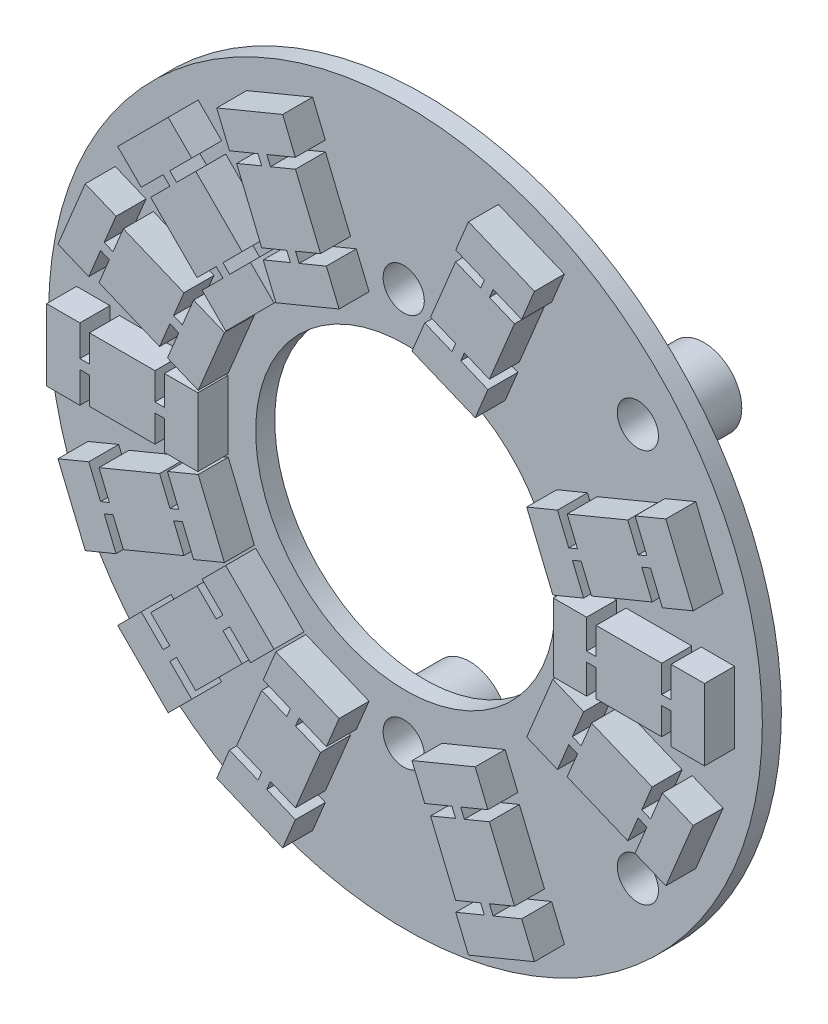
SolidWorks part; units mm, degrees
ref_plane "Front Plane" through (0, 0, 0) normal (0, 0, 1) x (1, 0, 0)
ref_plane "Top Plane" through (0, 0, 0) normal (0, 1, 0) x (1, 0, 0)
ref_plane "Right Plane" through (0, 0, 0) normal (1, 0, 0) x (0, 0, -1)
sketch "Sketch3" plane through (0, 0, 0) normal (0, 0, 1) x (1, 0, 0)
  line L12 (-1.6171, 12.9824) -> (-3.5525, 12.9824)
  line L13 (9.3448, 12.9824) -> (-1.6171, 12.9824)
  line L14 (10.3034, 12.9824) -> (9.3448, 12.9824)
  line L15 (12.3651, 9.967) -> (12.3651, 10.9208)
  line L16 (12.3651, -9.7668) -> (12.3651, 9.967)
  line L17 (12.3651, -10.7265) -> (12.3651, -9.7668)
  line L18 (9.3576, -12.7882) -> (10.3034, -12.7882)
  line L19 (-3.5398, -12.7882) -> (-1.6299, -12.7882)
  line L20 (-1.6299, -12.7882) -> (9.3576, -12.7882)
  line L21 (-10.1708, -12.7882) -> (-3.5398, -12.7882)
  line L22 (-12.2325, 10.9208) -> (-12.2325, -10.7265)
  line L23 (-3.5525, 12.9824) -> (-10.1708, 12.9824)
  line L34 (9.5245, 6.1678) -> (5.7246, 6.1678)
  line L35 (9.7306, -3.0873) -> (9.7306, 5.9617)
  line L36 (5.7246, -3.2934) -> (9.5245, -3.2934)
  line L37 (5.5184, 5.9617) -> (5.5184, -3.0873)
  line L38 (1.5664, -2.5118) -> (5.5184, -2.5118)
  line L39 (5.5184, 3.2608) -> (1.5664, 3.2608)
  line L40 (1.6413, -4.0348) -> (1.6413, 4.2118)
  line L41 (-6.6053, -4.0348) -> (1.6413, -4.0348)
  line L42 (-6.6053, 4.2118) -> (-6.6053, -4.0348)
  line L43 (1.6413, 4.2118) -> (-6.6053, 4.2118)
  circle A0 centre (-2.482, 0.0885) radius 19.05
  circle A1 centre (-2.5789, -10.4031) radius 1.1 construction
  circle A2 centre (9.9211, -10.4031) radius 1.1 construction
  circle A3 centre (-2.5789, 10.5969) radius 1.1 construction
  circle A4 centre (9.9211, 10.5969) radius 1.1 construction
  circle A5 centre (-2.5789, -10.4031) radius 1.1
  circle A6 centre (9.9211, -10.4031) radius 1.1
  circle A7 centre (-2.5789, 10.5969) radius 1.1
  arc A12 (12.3651, 10.9208) -> (10.3034, 12.9824) centre (10.3034, 10.9208) ccw
  arc A13 (10.3034, -12.7882) -> (12.3651, -10.7265) centre (10.3034, -10.7265) ccw
  arc A14 (-12.2325, -10.7265) -> (-10.1708, -12.7882) centre (-10.1708, -10.7265) ccw
  arc A15 (-10.1708, 12.9824) -> (-12.2325, 10.9208) centre (-10.1708, 10.9208) ccw
  circle A16 centre (9.9211, 10.5969) radius 1.1
  circle A21 centre (-2.482, 0.0885) radius 3.2986
  arc A22 (5.7246, 6.1678) -> (5.5184, 5.9617) centre (5.7246, 5.9617) ccw
  arc A23 (9.7306, 5.9617) -> (9.5245, 6.1678) centre (9.5245, 5.9617) ccw
  arc A24 (9.5245, -3.2934) -> (9.7306, -3.0873) centre (9.5245, -3.0873) ccw
  arc A25 (5.5184, -3.0873) -> (5.7246, -3.2934) centre (5.7246, -3.0873) ccw
  circle A26 centre (-2.482, 0.0885) radius 8.0005
  dimension "D1" = 38.1
extrude "Boss-Extrude1" add sketch "Sketch3" along normal blind 1.016
sketch "Sketch4" plane through (0, 0, 0) normal (0, 0, 1) x (1, 0, 0)
  line L0 (-21.532, 0.0885) -> (-10.4825, 0.0885) construction
  line L1 (-15.8231, 8.1122) -> (-12.5895, 6.7728)
  line L2 (-17.7572, -1.6115) -> (-14.2572, -1.6115)
  line L3 (-17.7572, -1.6115) -> (-17.7572, 1.7885)
  line L4 (-17.7572, 1.7885) -> (-14.2572, 1.7885)
  line L5 (-14.2572, -1.6115) -> (-14.2572, 1.7885)
  line L6 (-17.7572, -1.6115) -> (-14.2572, 1.7885) construction
  line L7 (-17.7572, 1.7885) -> (-14.2572, -1.6115) construction
  line L8 (-17.1242, 4.971) -> (-15.8231, 8.1122)
  line L9 (-17.1242, 4.971) -> (-13.8906, 3.6316)
  line L10 (-13.8906, 3.6316) -> (-12.5895, 6.7728)
  line L11 (-11.6162, 13.2144) -> (-9.1413, 10.7395)
  line L12 (-14.0203, 10.8102) -> (-11.6162, 13.2144)
  line L13 (-14.0203, 10.8102) -> (-11.5455, 8.3353)
  line L14 (-11.5455, 8.3353) -> (-9.1413, 10.7395)
  line L15 (-5.777, 16.3182) -> (-4.4376, 13.0847)
  line L16 (-8.9182, 15.0171) -> (-5.777, 16.3182)
  line L17 (-8.9182, 15.0171) -> (-7.5788, 11.7835)
  line L18 (-7.5788, 11.7835) -> (-4.4376, 13.0847)
  line L19 (0.8055, 16.9513) -> (0.8055, 13.4513) [skipped]
  line L20 (-2.5945, 16.9513) -> (0.8055, 16.9513) [skipped]
  line L21 (-2.5945, 16.9513) -> (-2.5945, 13.4513) [skipped]
  line L22 (-2.5945, 13.4513) -> (0.8055, 13.4513) [skipped]
  line L23 (7.1292, 15.0171) -> (5.7898, 11.7835)
  line L24 (3.988, 16.3182) -> (7.1292, 15.0171)
  line L25 (3.988, 16.3182) -> (2.6486, 13.0847)
  line L26 (2.6486, 13.0847) -> (5.7898, 11.7835)
  line L27 (12.2313, 10.8102) -> (9.7565, 8.3353) [skipped]
  line L28 (9.8272, 13.2144) -> (12.2313, 10.8102) [skipped]
  line L29 (9.8272, 13.2144) -> (7.3523, 10.7395) [skipped]
  line L30 (7.3523, 10.7395) -> (9.7565, 8.3353) [skipped]
  line L31 (15.3352, 4.971) -> (12.1016, 3.6316)
  line L32 (14.0341, 8.1122) -> (15.3352, 4.971)
  line L33 (14.0341, 8.1122) -> (10.8005, 6.7728)
  line L34 (10.8005, 6.7728) -> (12.1016, 3.6316)
  line L35 (15.9682, -1.6115) -> (12.4682, -1.6115)
  line L36 (15.9682, 1.7885) -> (15.9682, -1.6115)
  line L37 (15.9682, 1.7885) -> (12.4682, 1.7885)
  line L38 (12.4682, 1.7885) -> (12.4682, -1.6115)
  line L39 (14.0341, -7.9351) -> (10.8005, -6.5957)
  line L40 (15.3352, -4.7939) -> (14.0341, -7.9351)
  line L41 (15.3352, -4.7939) -> (12.1016, -3.4546)
  line L42 (12.1016, -3.4546) -> (10.8005, -6.5957)
  line L43 (9.8272, -13.0373) -> (7.3523, -10.5624) [skipped]
  line L44 (12.2313, -10.6331) -> (9.8272, -13.0373) [skipped]
  line L45 (12.2313, -10.6331) -> (9.7565, -8.1583) [skipped]
  line L46 (9.7565, -8.1583) -> (7.3523, -10.5624) [skipped]
  line L47 (3.988, -16.1411) -> (2.6486, -12.9076)
  line L48 (7.1292, -14.84) -> (3.988, -16.1411)
  line L49 (7.1292, -14.84) -> (5.7898, -11.6064)
  line L50 (5.7898, -11.6064) -> (2.6486, -12.9076)
  line L51 (-2.5945, -16.7742) -> (-2.5945, -13.2742) [skipped]
  line L52 (0.8055, -16.7742) -> (-2.5945, -16.7742) [skipped]
  line L53 (0.8055, -16.7742) -> (0.8055, -13.2742) [skipped]
  line L54 (0.8055, -13.2742) -> (-2.5945, -13.2742) [skipped]
  line L55 (-8.9182, -14.84) -> (-7.5788, -11.6064)
  line L56 (-5.777, -16.1411) -> (-8.9182, -14.84)
  line L57 (-5.777, -16.1411) -> (-4.4376, -12.9076)
  line L58 (-4.4376, -12.9076) -> (-7.5788, -11.6064)
  line L59 (-14.0203, -10.6331) -> (-11.5455, -8.1583)
  line L60 (-11.6162, -13.0373) -> (-14.0203, -10.6331)
  line L61 (-11.6162, -13.0373) -> (-9.1413, -10.5624)
  line L62 (-9.1413, -10.5624) -> (-11.5455, -8.1583)
  line L63 (-17.1242, -4.7939) -> (-13.8906, -3.4546)
  line L64 (-15.8231, -7.9351) -> (-17.1242, -4.7939)
  line L65 (-15.8231, -7.9351) -> (-12.5895, -6.5957)
  line L66 (-12.5895, -6.5957) -> (-13.8906, -3.4546)
  line L67 (-0.8945, 0.0885) -> (-14.2572, 1.7885) construction
  line L68 (-0.8945, 0.0885) -> (-12.5895, 6.7728) construction
  circle A0 centre (-2.482, 0.0885) radius 19.05 construction
  circle A1 centre (-2.482, 0.0885) radius 8.0005 construction
  point P7 (-16.0072, 0.0885)
  dimension "D1" = 3.5
  dimension "D2" = 3.4
  dimension "D4" = 22.5
  dimension "D3" = 16
sketch "Sketch5" plane through (-0.0742, 0.0026, -3.44) normal (0, 0, 1) x (1, 0, 0)
  circle A0 centre (-2.5047, 10.5942) radius 1.1
  circle A1 centre (9.9953, 10.5942) radius 1.1
  circle A2 centre (9.9953, -10.4058) radius 1.1
  circle A3 centre (-2.5047, -10.4058) radius 1.1
  circle A4 centre (-2.5047, -10.4058) radius 2.032
  circle A5 centre (9.9953, -10.4058) radius 2.032
  circle A6 centre (-2.5047, 10.5942) radius 2.032
  circle A7 centre (9.9953, 10.5942) radius 2.032
  dimension "D1" = 4.064
  dimension "D2" = 4.064
  dimension "D3" = 4.064
  dimension "D4" = 4.064
extrude "Boss-Extrude3" add sketch "Sketch5" against normal blind 2.5 from surface at 3.44 contours A6 | A7 | A5 | A4 | A1 | A0 | A3 | A2 starting at face at (5.5184, 0.0885, 0)
sketch "Sketch9" plane through (0, 0, 0) normal (0, 0, 1) x (1, 0, 0)
  line L0 (-10.4825, 0.0885) -> (-21.532, 0.0885) construction
  line L1 (-21.4402, 0.0885) -> (-20.9322, 0.0885) construction
  line L2 (-17.7572, -1.6115) -> (-14.2572, -1.6115)
  line L3 (-17.7572, -1.6115) -> (-17.7572, -0.1655)
  line L4 (-17.7572, 1.7885) -> (-14.2572, 1.7885)
  line L5 (-14.2572, -1.6115) -> (-14.2572, -0.1655)
  line L6 (-17.7572, -1.6115) -> (-14.2572, 1.7885) construction
  line L7 (-17.7572, 1.7885) -> (-14.2572, -1.6115) construction
  line L8 (-13.7492, -1.7361) -> (-11.9712, -1.7361)
  line L9 (-13.7492, -1.7361) -> (-13.7492, -0.1655)
  line L10 (-13.7492, 1.9132) -> (-11.9712, 1.9132)
  line L11 (-11.9712, -1.7361) -> (-11.9712, 1.9132)
  line L12 (-13.7492, -1.7361) -> (-11.9712, 1.9132) construction
  line L13 (-13.7492, 1.9132) -> (-11.9712, -1.7361) construction
  line L14 (-20.0432, -1.8165) -> (-18.2652, -1.8165)
  line L15 (-20.0432, -1.8165) -> (-20.0432, 1.9935)
  line L16 (-20.0432, 1.9935) -> (-18.2652, 1.9935)
  line L17 (-18.2652, -1.8165) -> (-18.2652, -0.1655)
  line L18 (-20.0432, -1.8165) -> (-18.2652, 1.9935) construction
  line L19 (-20.0432, 1.9935) -> (-18.2652, -1.8165) construction
  line L20 (-21.4402, 0.0885) -> (-20.9322, 0.0885) construction
  line L22 (-18.2652, 0.3425) -> (-17.7572, 0.3425)
  line L23 (-18.2652, -0.1655) -> (-17.7572, -0.1655)
  line L24 (-17.4322, 0.0885) -> (-16.9242, 0.0885) construction
  line L26 (-14.2572, -0.1655) -> (-13.7492, -0.1655)
  line L27 (-14.2572, 0.3425) -> (-13.7492, 0.3425)
  line L28 (-18.2652, 0.3425) -> (-18.2652, 1.9935)
  line L29 (-17.7572, 0.3425) -> (-17.7572, 1.7885)
  line L30 (-14.2572, 0.3425) -> (-14.2572, 1.7885)
  line L31 (-13.7492, 0.3425) -> (-13.7492, 1.9132)
  circle A0 centre (-2.482, 0.0885) radius 8.0005 construction
  circle A1 centre (-2.482, 0.0885) radius 19.05 construction
  point P7 (-16.0072, 0.0885)
  point P12 (-12.8602, 0.0885)
  point P17 (-19.1542, 0.0885)
  dimension "D1" = 1.778
  dimension "D2" = 3.5
  dimension "D3" = 3.4
  dimension "D4" = 3.81
  dimension "D5" = 0.508
  dimension "D6" = 0.508
  dimension "D7" = 0.508
  dimension "D8" = 0.508
extrude "Boss-Extrude4" add sketch "Sketch9" along normal blind 1.6 from surface at 1.016 contours L14 L17 L16 L15 | L2 L5 L4 L3 | L8 L11 L10 L9 starting at face at (5.5184, 0.0885, 1.016)
pattern_circular "CirPattern1" count 16 over 360 about axis through (-2.482, 0.0885, 0) along (0, 0, 1) skipping 4, 6, 10, 12 of "Boss-Extrude4"
